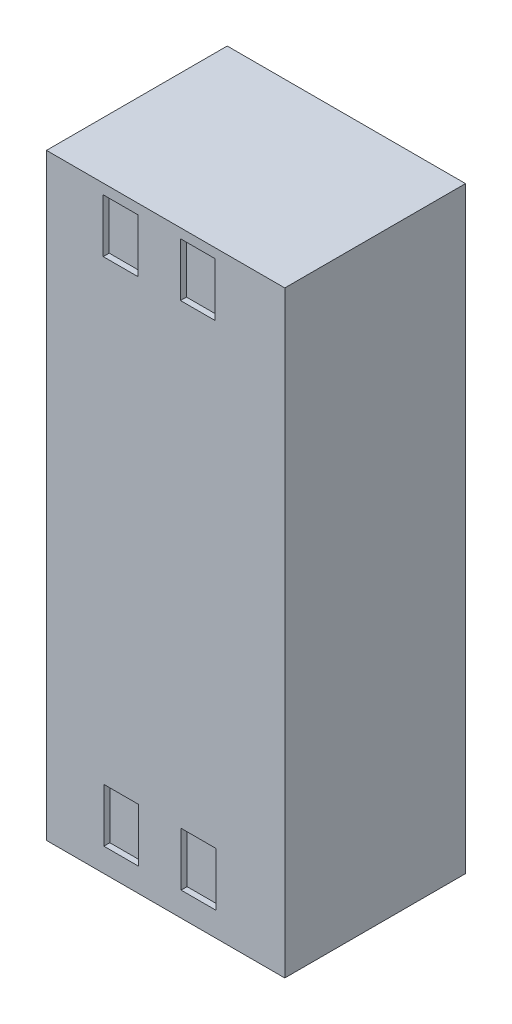
SolidWorks part; units mm, degrees
material "PVC 0.007 Plasticized"
ref_plane "Front Plane" through (0, 0, 0) normal (0, 0, 1) x (1, 0, 0)
ref_plane "Top Plane" through (0, 0, 0) normal (0, 1, 0) x (1, 0, 0)
ref_plane "Right Plane" through (0, 0, 0) normal (1, 0, 0) x (0, 0, -1)
other "plastic"
sketch "Sketch1" plane through (0, 0, 0) normal (0, 0, 1) x (1, 0, 0)
  line L5 (0, 0) -> (50.5659, 0)
  line L6 (0, 0) -> (0, -126.8123)
  line L7 (0, -126.8123) -> (50.5659, -126.8123)
  line L8 (50.5659, 0) -> (50.5659, -126.8123)
  dimension "D1" = 50.5659
  dimension "D2" = 126.8123
extrude "Boss-Extrude2" add sketch "Sketch1" along normal blind 38.354
shell "Shell1" thickness 2.54
sketch "Sketch5" plane through (0, 0, 38.354) normal (0, 0, 1) x (1, 0, 0)
  line L0 (28.5658, -110.3) -> (35.9409, -110.3)
  line L1 (12.1716, -110.4217) -> (19.5468, -110.4217)
  line L2 (12.1716, -110.4217) -> (12.1716, -121.7836)
  line L3 (12.1716, -121.7836) -> (19.5468, -121.7836)
  line L4 (19.5468, -110.4217) -> (19.5468, -121.7836)
  line L5 (28.5658, -110.3) -> (28.5658, -121.6619)
  line L6 (28.5658, -121.6619) -> (35.9409, -121.6619)
  line L7 (35.9409, -110.3) -> (35.9409, -121.6619)
  line L8 (28.4365, -2.0203) -> (35.8116, -2.0203)
  line L9 (12.0424, -2.142) -> (19.4175, -2.142)
  line L10 (12.0424, -2.142) -> (12.0424, -13.5039)
  line L11 (12.0424, -13.5039) -> (19.4175, -13.5039)
  line L12 (19.4175, -2.142) -> (19.4175, -13.5039)
  line L13 (28.4365, -2.0203) -> (28.4365, -13.3822)
  line L14 (28.4365, -13.3822) -> (35.8116, -13.3822)
  line L15 (35.8116, -2.0203) -> (35.8116, -13.3822)
extrude "Cut-Extrude3" cut sketch "Sketch5" against normal blind 1.27
sketch "Sketch8" plane through (0, 0, 0) normal (0, 0, -1) x (-1, 0, 0)
  line L1 (-43.308, -99.8985) -> (-7.5997, -99.8985)
  line L2 (-43.308, -99.8985) -> (-43.308, -118.9272)
  line L3 (-43.308, -118.9272) -> (-7.5997, -118.9272)
  line L4 (-7.5997, -99.8985) -> (-7.5997, -118.9272)
extrude "Cut-Extrude4" cut sketch "Sketch8" against normal blind 1.27 contours L2 L1 L4 L3
